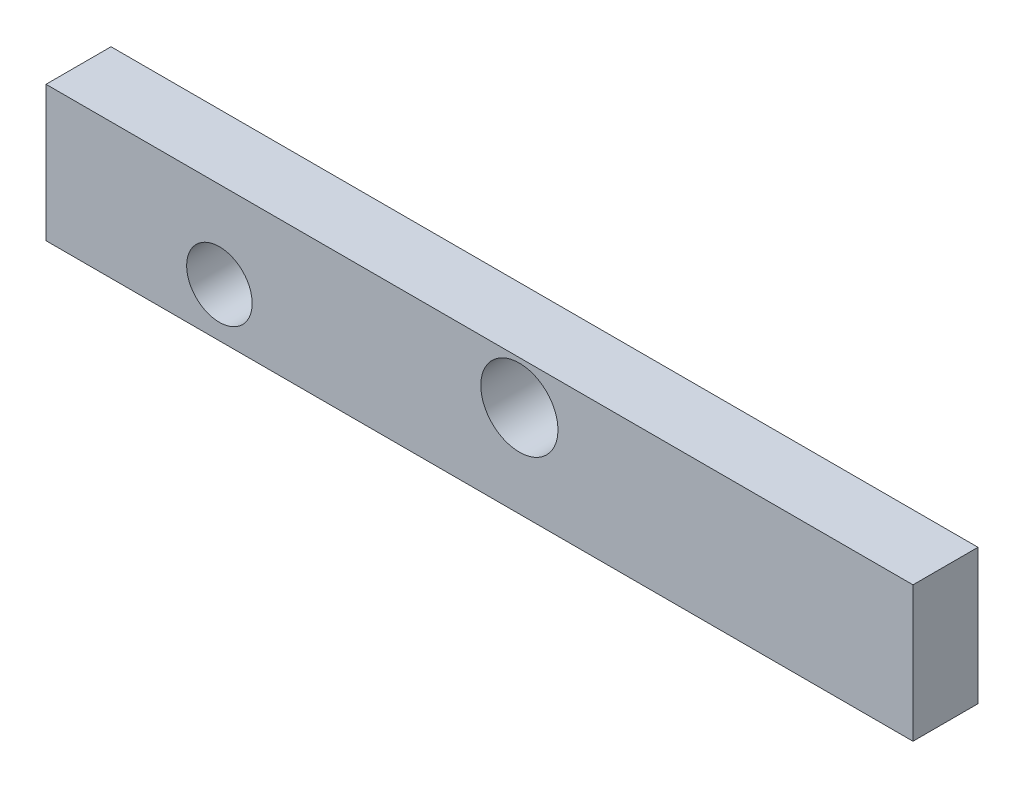
SolidWorks part; units mm, degrees
ref_plane "Front Plane" through (0, 0, 0) normal (0, 0, 1) x (1, 0, 0)
ref_plane "Top Plane" through (0, 0, 0) normal (0, 1, 0) x (1, 0, 0)
ref_plane "Right Plane" through (0, 0, 0) normal (1, 0, 0) x (0, 0, -1)
sketch "Sketch1" plane through (0, 0, 0) normal (0, 0, 1) x (1, 0, 0)
  line L1 (63.5, -22.225) -> (-63.5, -22.225)
  line L2 (63.5, -22.225) -> (63.5, 22.225)
  line L3 (63.5, 22.225) -> (-63.5, 22.225)
  line L4 (-63.5, -22.225) -> (-63.5, 22.225)
  line L5 (63.5, -22.225) -> (-63.5, 22.225) construction
  line L6 (63.5, 22.225) -> (-63.5, -22.225) construction
  point P0 (0, 0)
  dimension "D1" = 127
  dimension "D2" = 44.45
extrude "Boss-Extrude1" add sketch "Sketch1" along normal blind 9.525
sketch "Sketch3" plane through (0, 0, 9.525) normal (0, 0, 1) x (1, 0, 0)
  line L0 (-48.998, 18.1039) -> (-27.202, -13.0239) construction
  line L1 (63.5, 22.225) -> (-63.5, 22.225) construction
  circle A0 centre (-38.1, 2.54) radius 19 construction
  point P8 (-48.998, 18.1039)
  point P9 (-27.202, -13.0239)
  dimension "D1" = 38
  dimension "D2" = 38.1
  dimension "D3" = 2.54
  dimension "D4" = 55
hole_wizard "Tap Drill for #8-32 Tap1" positions "Sketch3" profile "Sketch5" hole size "#8-32" standard "ANSI Inch"
sketch "Sketch5" plane through (-27.202, -13.0239, 6.35) normal (1, 0, 0) x (0, -1, 0)
  line L0 (0, 0) -> (0, 6.35)
  line L1 (0, 6.35) -> (1.7272, 6.35)
  line L2 (1.7272, 6.35) -> (1.7272, 0)
  line L5 (1.7272, 0) -> (0, 0)
  line L11 (0, -6.35) -> (0, 107.95) construction
  dimension "Thru Hole Dia." = 3.4544
  dimension "Thru Hole Depth" = 6.35
sketch "Sketch6" plane through (0, 0, 0) normal (0, 0, 1) x (1, 0, 0)
  line L0 (-42.5809, 9.9387) -> (-33.6191, 9.1113) construction
  line L1 (63.5, 22.225) -> (-63.5, 22.225) construction
  line L2 (-63.5, 22.225) -> (-63.5, -22.225) construction
  circle A0 centre (-38.1, 9.525) radius 4.5 construction
  circle A1 centre (-38.1, 9.525) radius 4.8
  point P8 (-42.5809, 9.9387)
  point P9 (-33.6191, 9.1113)
  dimension "D1" = 9
  dimension "D2" = 12.7
  dimension "D3" = 9.6
  dimension "D4" = 25.4
extrude "Cut-Extrude1" cut sketch "Sketch6" along normal through all contours A1
sketch "Sketch10" plane through (0, 0, 9.525) normal (0, 0, 1) x (1, 0, 0)
  circle A0 centre (-46.1155, -16.764) radius 2.286
  circle A1 centre (-38.1, 9.525) radius 4.8 construction
  dimension "D1" = 4.572
  dimension "D2" = 26.289
extrude "Cut-Extrude2" cut sketch "Sketch10" against normal blind 3.81
sketch "Sketch13" plane through (0, 0, 0) normal (0, 0, -1) x (-1, 0, 0)
  line L0 (50.8, -22.225) -> (-50.8, -22.225) construction
  line L1 (-63.5, 2.3765) -> (63.5, 2.3765)
  line L2 (-63.5, 2.3765) -> (-63.5, -46.8265)
  line L3 (-63.5, -46.8265) -> (63.5, -46.8265)
  line L4 (63.5, 2.3765) -> (63.5, -46.8265)
  line L5 (-63.5, 2.3765) -> (63.5, -46.8265) construction
  line L6 (-63.5, -46.8265) -> (63.5, 2.3765) construction
  line L7 (-63.5, -22.225) -> (-63.5, 22.225) construction
  point P0 (0, -22.225)
extrude "Cut-Extrude3" cut sketch "Sketch13" against normal through all
sketch "Sketch14" plane through (0, 0, 0) normal (0, 0, -1) x (-1, 0, 0)
  line L0 (-50.8, 14.3689) -> (-1.0961, 14.3689)
  line L1 (6.4513, 22.8295) -> (-0.3386, 15.218)
  line L2 (10.8191, 27.7258) -> (-0.3386, 15.218) construction
  line L3 (-0.3386, 15.218) -> (-1.0961, 14.3689)
  line L4 (6.4513, 22.8295) -> (6.4513, 26.3693)
  line L5 (6.4513, 26.3693) -> (-61.1176, 26.3693)
  line L6 (-61.1176, 26.3693) -> (-61.1176, 13.2924)
  line L7 (-61.1176, 13.2924) -> (-50.8, 14.3689)
sketch "Sketch15" plane through (0, 0, 0) normal (0, 0, -1) x (-1, 0, 0)
  circle A0 centre (-5.842, 15.875) radius 5.6521
  circle A1 centre (38.1, 9.525) radius 4.8 construction
  dimension "D1" = 43.942
  dimension "D2" = 6.35
extrude "Cut-Extrude4" cut sketch "Sketch15" against normal through all
